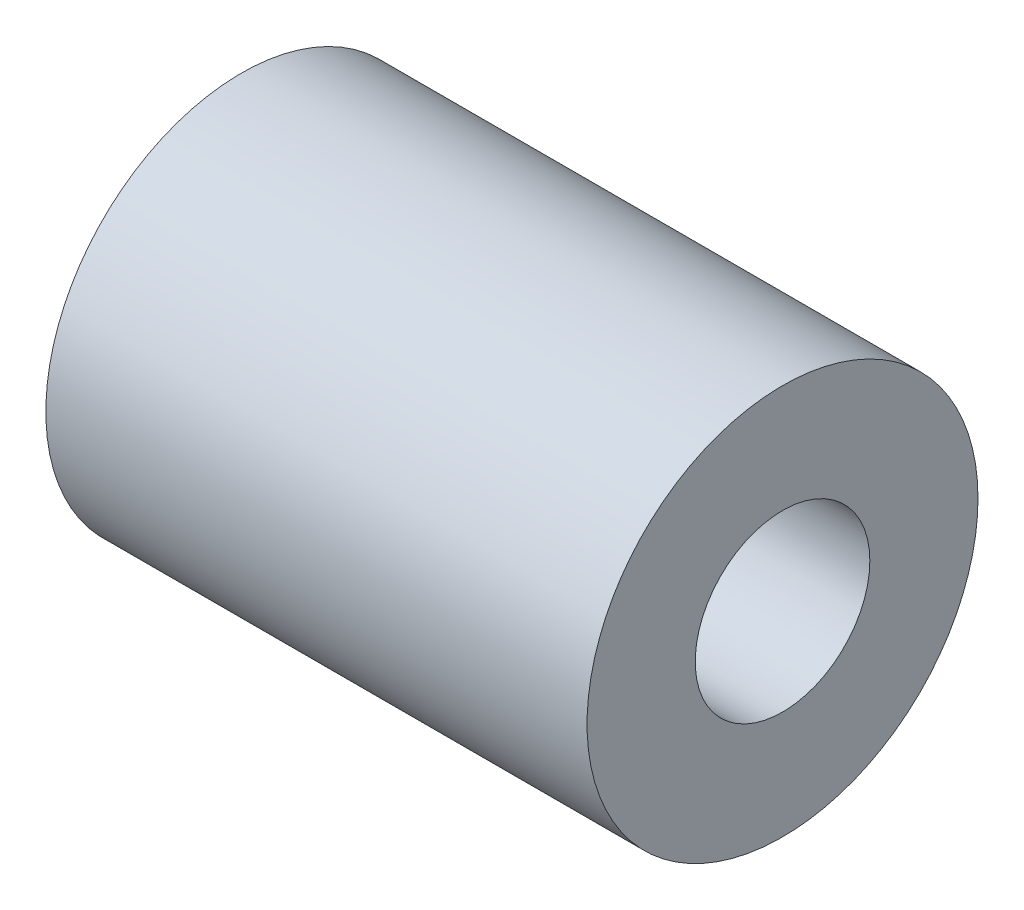
SolidWorks part; units mm, degrees
ref_plane "Front Plane" through (0, 0, 0) normal (0, 0, 1) x (1, 0, 0)
ref_plane "Top Plane" through (0, 0, 0) normal (0, 1, 0) x (1, 0, 0)
ref_plane "Right Plane" through (0, 0, 0) normal (1, 0, 0) x (0, 0, -1)
sketch "Sketch1" plane through (0, 0, 0) normal (1, 0, 0) x (0, 0, -1)
  circle A0 centre (0, 0) radius 2.5527
  circle A1 centre (0, 0) radius 5.715
  point P4 (0, 0)
  dimension "D1" = 5.1054
  dimension "D2" = 11.43
extrude "Boss-Extrude1" add sketch "Sketch1" along normal blind 15.8242
